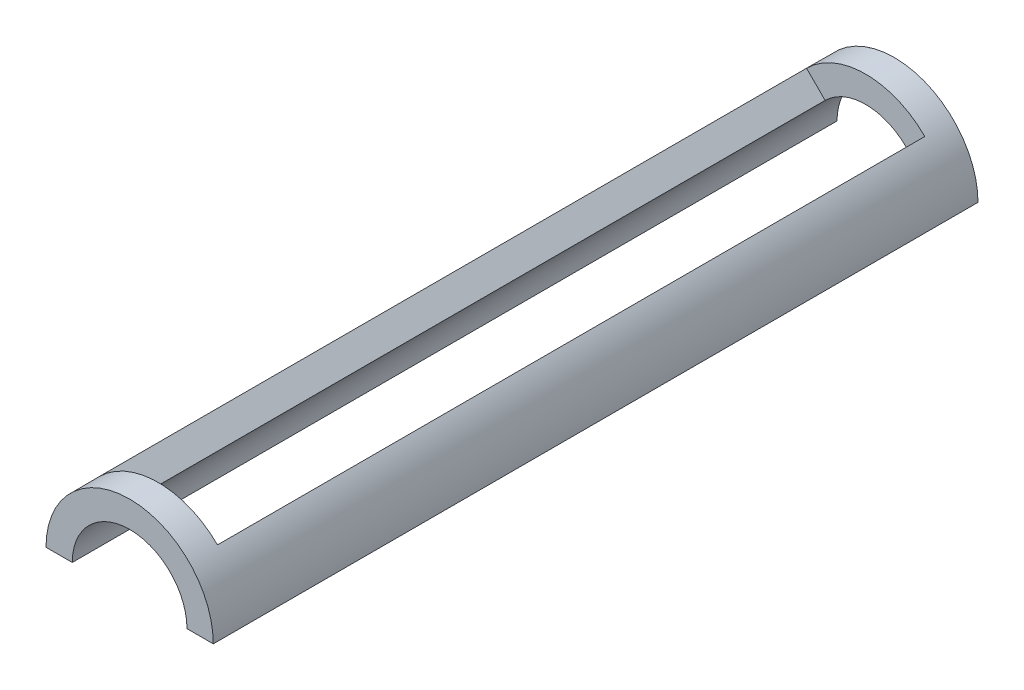
SolidWorks part; units mm, degrees
ref_plane "Front Plane" through (0, 0, 0) normal (0, 0, 1) x (1, 0, 0)
ref_plane "Top Plane" through (0, 0, 0) normal (0, 1, 0) x (1, 0, 0)
ref_plane "Right Plane" through (0, 0, 0) normal (1, 0, 0) x (0, 0, -1)
sketch "Sketch1" plane through (0, 0, 0) normal (0, 0, 1) x (1, 0, 0)
  line L5 (17.5, 0) -> (12, 0)
  line L6 (-12, 0) -> (-17.5, 0)
  arc A0 (12, 0) -> (-12, 0) centre (0, 0) ccw
  arc A1 (17.5, 0) -> (-17.5, 0) centre (0, 0) ccw
  dimension "D1" = 24
  dimension "D2" = 35
extrude "Boss-Extrude1" add sketch "Sketch1" along normal mid plane 160
ref_plane "Plane1" through (0, 17.5, 0) normal (0, 1, 0) x (1, 0, 0)
sketch "Sketch4" plane through (0, 0, 0) normal (0, 0, 1) x (1, 0, 0)
  line L0 (0, 0) -> (12.3744, 12.3744)
  line L1 (0, -9.625) -> (0, 9.625) construction
  line L2 (0, 0) -> (-12.3744, 12.3744)
  line L3 (19.25, 0) -> (-19.25, 0) construction
  arc A0 (12.3744, 12.3744) -> (-12.3744, 12.3744) centre (0, 0) ccw
  point P1 (0, 0)
  point P5 (0, 0)
  point P7 (0, 0)
  dimension "D1" = 35
  dimension "D2" = 90
extrude "Cut-Extrude3" cut sketch "Sketch4" against normal mid plane 148
